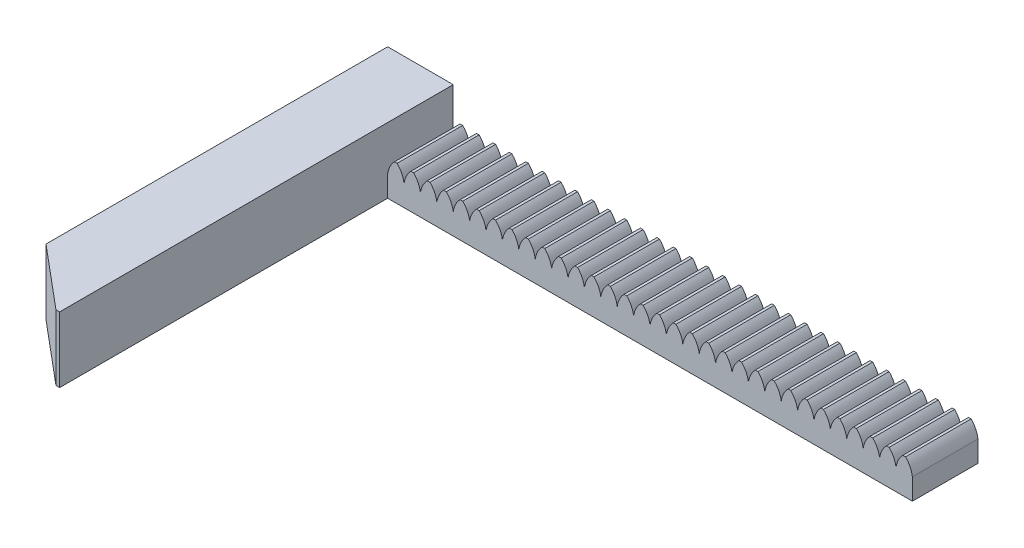
SolidWorks part; units mm, degrees
ref_plane "Front Plane" through (0, 0, 0) normal (0, 0, 1) x (1, 0, 0)
ref_plane "Top Plane" through (0, 0, 0) normal (0, 1, 0) x (1, 0, 0)
ref_plane "Right Plane" through (0, 0, 0) normal (1, 0, 0) x (0, 0, -1)
sketch "Sketch1" plane through (0, 0, 0) normal (0, 1, 0) x (1, 0, 0)
  line L0 (-50, -47.0858) -> (-40.5683, -55)
  line L5 (-40, 5) -> (40, 5)
  line L7 (-40, -5) -> (40, -5)
  line L8 (40, 5) -> (40, -5)
  line L9 (-40, 5) -> (40, -5) construction
  line L10 (-40, -5) -> (40, 5) construction
  line L11 (-40, 5) -> (-50, 5)
  line L12 (-40, -5) -> (-40, -55)
  line L13 (-40, -55) -> (-40.5683, -55)
  line L14 (-50, 5) -> (-50, -47.0858)
  point P0 (0, 0)
  dimension "D1" = 10
  dimension "D2" = 80
  dimension "D3" = 10
  dimension "D4" = 60
extrude "Boss-Extrude1" add sketch "Sketch1" along normal blind 10
sketch "Sketch5" plane through (0, 0, 5) normal (0, 0, 1) x (1, 0, 0)
  line L1 (40, 10) -> (37.5, 10)
  line L2 (40, 10) -> (40, 3.2214)
  line L4 (37.5, 10) -> (37.5, 3.2214)
  line L5 (38.75, 0) -> (38.75, 10) construction
  line L6 (37.5, 10) -> (40, 10)
  line L7 (-40, 10) -> (-40, 5)
  line L8 (38.55, 5.342) -> (38.95, 5.342)
  line L9 (40, 10) -> (40, 5)
  arc A0 (38.55, 5.342) -> (37.5, 3.2214) centre (41.214, 2.7027) ccw
  arc A1 (38.95, 5.342) -> (40, 3.2214) centre (36.286, 2.7027) cw
  dimension "D6" = 3.75
  dimension "D3" = 80
  dimension "D4" = 5
  dimension "D5" = 0.2
extrude "Cut-Extrude4" cut sketch "Sketch5" against normal blind 10 contours L5 L8 A1 L9 L2 | L8 L5 L6 L4 A0
pattern_linear "LPattern2" count 32 spacing 2.5 along (-1, 0, 0) of "Cut-Extrude4"
